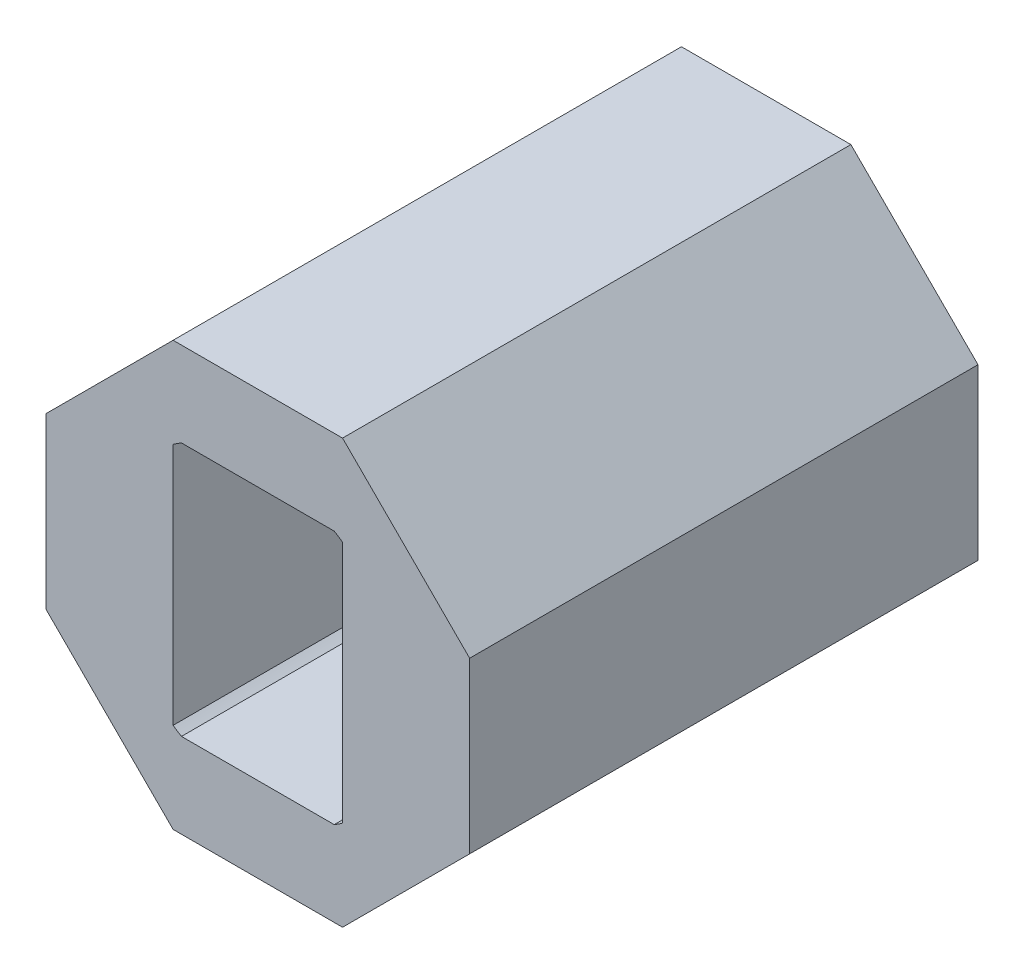
SolidWorks part; units mm, degrees
ref_plane "Front Plane" through (0, 0, 0) normal (1, 0, 0) x (0, 1, 0)
ref_plane "Top Plane" through (0, 0, 0) normal (0, 0, 1) x (0, 1, 0)
ref_plane "Right Plane" through (0, 0, 0) normal (0, 1, 0) x (-1, 0, 0)
sketch "Sketch1" plane through (0, 0, 0) normal (0, 0, 1) x (0, 1, 0)
  line L0 (3, 0) -> (0, -3)
  line L1 (3, 0) -> (7, 0)
  line L2 (0, -3) -> (0, -7)
  line L3 (3, -10) -> (7, -10)
  line L4 (10, -3) -> (10, -7)
  line L5 (0, -7) -> (3, -10)
  line L6 (7, -10) -> (10, -7)
  line L7 (10, -3) -> (7, 0)
  line L9 (2.1277, -3) -> (7.8723, -3)
  line L10 (2, -3.1972) -> (2, -6.8028)
  line L11 (2.1277, -7) -> (7.8723, -7)
  line L12 (8, -3.1972) -> (8, -6.8028)
  circle A0 centre (5, -5) radius 3.5
  dimension "D11" = 7
  dimension "D3" = 4
  dimension "D4" = 4
  dimension "D5" = 4
  dimension "D6" = 4
  dimension "D13" = 2
  dimension "D14" = 5
  dimension "D16" = 3
extrude "Boss-Extrude1" add sketch "Sketch1" along normal blind 12 contours L4 L7 L1 L0 L2 L5 L3 L6 A0 | L9 A0 | L11 A0 | L10 A0 | L12 A0
